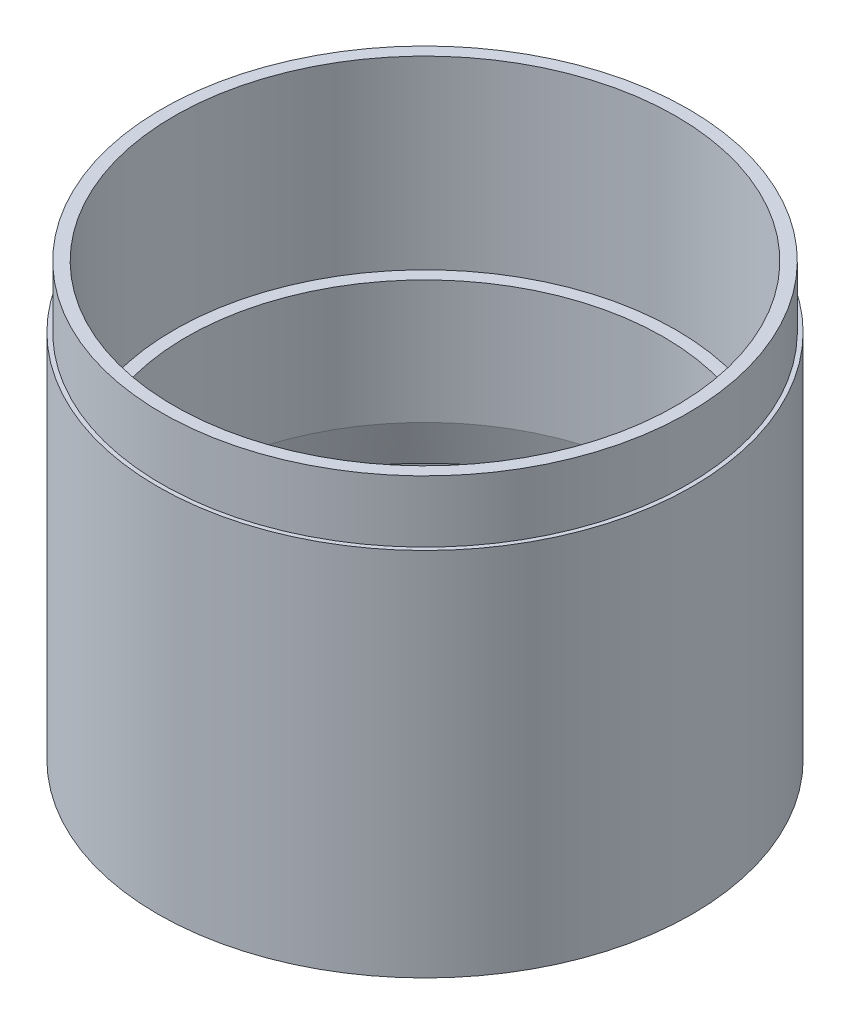
SolidWorks part; units mm, degrees
material "HYPALON"
ref_plane "Front Plane" through (0, 0, 0) normal (0, 0, 1) x (1, 0, 0)
ref_plane "Top Plane" through (0, 0, 0) normal (0, 1, 0) x (1, 0, 0)
ref_plane "Right Plane" through (0, 0, 0) normal (1, 0, 0) x (0, 0, -1)
sketch "Szkic1" plane through (0, 0, 0) normal (0, 0, 1) x (1, 0, 0)
  line L0 (0, 0) -> (-65, 0)
  line L1 (-65, 0) -> (-65, 20)
  line L2 (-62, 20) -> (-60, 20)
  line L3 (-58, 30) -> (-58, 60)
  line L4 (-62, 20) -> (-62, 0)
  line L5 (-58, 60) -> (-61, 60)
  line L6 (-61, 60) -> (-61, 105)
  line L7 (-65, 20) -> (-65, 90)
  line L8 (-65, 90) -> (-64, 90)
  line L9 (-64, 90) -> (-64, 105)
  line L10 (-64, 105) -> (-61, 105)
  line L11 (-64, 90) -> (-61, 90)
  line L12 (-60, 20) -> (-58, 30)
  line L13 (0, 0) -> (0, 22.4148)
  dimension "D1" = 65
  dimension "D2" = 20
  dimension "D3" = 62
  dimension "D4" = 7
  dimension "D5" = 10
  dimension "D6" = 3
  dimension "D7" = 1
  dimension "D8" = 15
  dimension "D9" = 85
  dimension "D10" = 40
  dimension "D13" = 2
revolve "Obrót1" add sketch "Szkic1" angle 360 about L13
